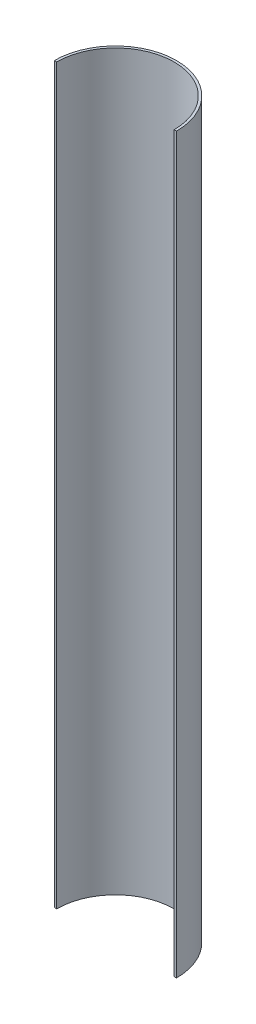
SolidWorks part; units mm, degrees
ref_plane "Front Plane" through (0, 0, 0) normal (0, 0, 1) x (1, 0, 0)
ref_plane "Top Plane" through (0, 0, 0) normal (0, 1, 0) x (1, 0, 0)
ref_plane "Right Plane" through (0, 0, 0) normal (1, 0, 0) x (0, 0, -1)
sketch "Sketch2" plane through (0, 0, 0) normal (0, 1, 0) x (1, 0, 0)
  line L0 (-125, 0) -> (125, 0)
  circle A0 centre (0, 0) radius 120
  circle A1 centre (0, 0) radius 125
  dimension "D1" = 240
  dimension "D2" = 250
extrude "Boss-Extrude1" add sketch "Sketch2" along normal blind 1500 contours L0 A1 A0
